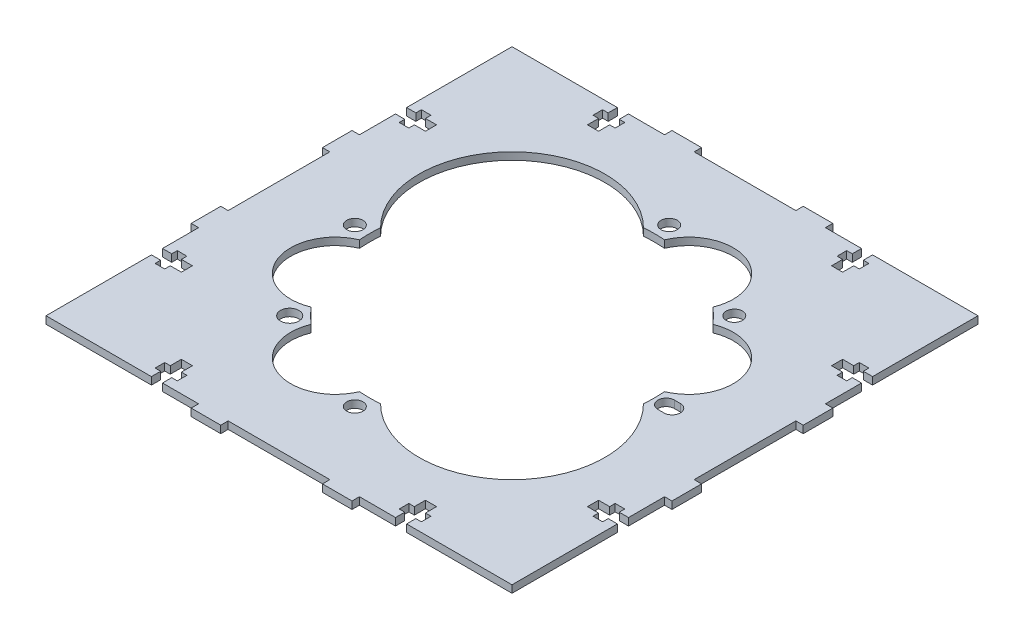
SolidWorks part; units mm, degrees
ref_plane "前视基准面" through (0, 0, 0) normal (0, 0, 1) x (1, 0, 0)
ref_plane "上视基准面" through (0, 0, 0) normal (0, 1, 0) x (1, 0, 0)
ref_plane "右视基准面" through (0, 0, 0) normal (1, 0, 0) x (0, 0, -1)
sketch "草图1" plane through (0, 0, 0) normal (0, 1, 0) x (1, 0, 0)
  line L529 (159.7547, 48.9956) -> (150.0047, 48.9956)
  line L530 (147.0047, 46.4956) -> (145.5047, 46.4956)
  line L531 (150.0047, 46.4956) -> (151.5047, 46.4956)
  line L532 (150.0047, 48.9956) -> (150.0047, 46.4956)
  line L533 (145.5047, 46.4956) -> (145.5047, 43.8956)
  line L534 (145.5047, 43.8956) -> (147.0047, 43.8956)
  line L535 (147.0047, 43.8956) -> (147.0047, 40.8956)
  line L536 (150.0047, 40.8956) -> (147.0047, 40.8956)
  line L537 (150.0047, 43.8956) -> (150.0047, 40.8956)
  line L538 (151.5047, 43.8956) -> (150.0047, 43.8956)
  line L539 (151.5047, 46.4956) -> (151.5047, 43.8956)
  line L540 (147.0047, 46.4956) -> (147.0047, 48.9956)
  line L541 (213.0047, 48.9956) -> (203.2547, 48.9956)
  line L542 (211.5047, 46.4956) -> (211.5047, 43.8956)
  line L543 (216.0047, 46.4956) -> (216.0047, 48.9956)
  line L544 (211.5047, 43.8956) -> (213.0047, 43.8956)
  line L545 (213.0047, 43.8956) -> (213.0047, 40.8956)
  line L546 (213.0047, 40.8956) -> (216.0047, 40.8956)
  line L547 (216.0047, 43.8956) -> (216.0047, 40.8956)
  line L548 (217.5047, 43.8956) -> (216.0047, 43.8956)
  line L549 (217.5047, 46.4956) -> (217.5047, 43.8956)
  line L550 (213.0047, 48.9956) -> (213.0047, 46.4956)
  line L551 (213.0047, 46.4956) -> (211.5047, 46.4956)
  line L552 (216.0047, 46.4956) -> (217.5047, 46.4956)
  line L554 (203.2547, 48.9956) -> (203.2547, 50.9956)
  line L555 (195.2547, 50.9956) -> (195.2547, 48.9956)
  line L556 (195.2547, 48.9956) -> (167.7547, 48.9956)
  line L557 (159.7547, 50.9956) -> (167.7547, 50.9956)
  line L558 (167.7547, 48.9956) -> (167.7547, 50.9956)
  line L559 (159.7547, 50.9956) -> (159.7547, 48.9956)
  line L560 (203.2547, 50.9956) -> (195.2547, 50.9956)
  line L598 (217.0047, 48.9956) -> (216.0047, 48.9956)
  line L602 (244.5047, 7.7456) -> (244.5047, 17.4956)
  line L603 (242.0047, 20.4956) -> (242.0047, 21.9956)
  line L604 (147.0047, 48.9956) -> (138.6047, 48.9956)
  line L605 (242.0047, 17.4956) -> (242.0047, 15.9956)
  line L606 (244.5047, 17.4956) -> (242.0047, 17.4956)
  line L607 (181.5047, -77.0044) -> (181.5047, -65.0044) construction
  line L608 (242.0047, 21.9956) -> (239.4047, 21.9956)
  line L609 (138.6047, 48.9956) -> (133.5047, 48.9956)
  line L613 (217.0047, 48.9956) -> (229.5047, 48.9956)
  line L614 (239.4047, 21.9956) -> (239.4047, 20.4956)
  line L615 (239.4047, 20.4956) -> (236.4047, 20.4956)
  line L616 (236.4047, 17.4956) -> (236.4047, 20.4956)
  line L617 (239.4047, 17.4956) -> (236.4047, 17.4956)
  line L618 (239.4047, 15.9956) -> (239.4047, 17.4956)
  line L619 (242.0047, 15.9956) -> (239.4047, 15.9956)
  line L620 (242.0047, 20.4956) -> (244.5047, 20.4956)
  line L621 (244.5047, -45.5044) -> (244.5047, -35.7544)
  line L622 (242.0047, -44.0044) -> (239.4047, -44.0044)
  line L623 (242.0047, -48.5044) -> (244.5047, -48.5044)
  line L624 (239.4047, -44.0044) -> (239.4047, -45.5044)
  line L625 (239.4047, -45.5044) -> (236.4047, -45.5044)
  line L626 (236.4047, -45.5044) -> (236.4047, -48.5044)
  line L627 (239.4047, -48.5044) -> (236.4047, -48.5044)
  line L628 (239.4047, -50.0044) -> (239.4047, -48.5044)
  line L629 (242.0047, -50.0044) -> (239.4047, -50.0044)
  line L630 (244.5047, -45.5044) -> (242.0047, -45.5044)
  line L631 (242.0047, -45.5044) -> (242.0047, -44.0044)
  line L632 (242.0047, -48.5044) -> (242.0047, -50.0044)
  line L633 (244.5047, -35.7544) -> (246.5047, -35.7544)
  line L634 (246.5047, -27.7544) -> (244.5047, -27.7544)
  line L635 (244.5047, -27.7544) -> (244.5047, -0.2544)
  line L636 (246.5047, 7.7456) -> (246.5047, -0.2544)
  line L637 (244.5047, -0.2544) -> (246.5047, -0.2544)
  line L638 (246.5047, 7.7456) -> (244.5047, 7.7456)
  line L639 (246.5047, -35.7544) -> (246.5047, -27.7544)
  line L640 (244.5047, -49.5044) -> (244.5047, -48.5044)
  line L641 (244.5047, 20.4956) -> (244.5047, 28.8956)
  line L642 (244.5047, 28.8956) -> (244.5047, 33.9956)
  line L643 (244.5047, -49.5044) -> (244.5047, -62.0044)
  line L644 (203.2547, -77.0044) -> (213.0047, -77.0044)
  line L645 (216.0047, -74.5044) -> (217.5047, -74.5044)
  line L646 (213.0047, -74.5044) -> (211.5047, -74.5044)
  line L647 (213.0047, -77.0044) -> (213.0047, -74.5044)
  line L648 (217.5047, -74.5044) -> (217.5047, -71.9044)
  line L649 (217.5047, -71.9044) -> (216.0047, -71.9044)
  line L650 (216.0047, -71.9044) -> (216.0047, -68.9044)
  line L651 (213.0047, -68.9044) -> (216.0047, -68.9044)
  line L652 (213.0047, -71.9044) -> (213.0047, -68.9044)
  line L653 (211.5047, -71.9044) -> (213.0047, -71.9044)
  line L654 (211.5047, -74.5044) -> (211.5047, -71.9044)
  line L655 (216.0047, -74.5044) -> (216.0047, -77.0044)
  line L656 (150.0047, -77.0044) -> (159.7547, -77.0044)
  line L657 (151.5047, -74.5044) -> (151.5047, -71.9044)
  line L658 (147.0047, -74.5044) -> (147.0047, -77.0044)
  line L659 (151.5047, -71.9044) -> (150.0047, -71.9044)
  line L660 (150.0047, -71.9044) -> (150.0047, -68.9044)
  line L661 (150.0047, -68.9044) -> (147.0047, -68.9044)
  line L662 (147.0047, -71.9044) -> (147.0047, -68.9044)
  line L663 (145.5047, -71.9044) -> (147.0047, -71.9044)
  line L664 (145.5047, -74.5044) -> (145.5047, -71.9044)
  line L665 (150.0047, -77.0044) -> (150.0047, -74.5044)
  line L666 (150.0047, -74.5044) -> (151.5047, -74.5044)
  line L667 (147.0047, -74.5044) -> (145.5047, -74.5044)
  line L668 (159.7547, -77.0044) -> (159.7547, -79.0044)
  line L669 (167.7547, -79.0044) -> (167.7547, -77.0044)
  line L670 (167.7547, -77.0044) -> (195.2547, -77.0044)
  line L671 (203.2547, -79.0044) -> (195.2547, -79.0044)
  line L672 (195.2547, -77.0044) -> (195.2547, -79.0044)
  line L673 (203.2547, -79.0044) -> (203.2547, -77.0044)
  line L674 (159.7547, -79.0044) -> (167.7547, -79.0044)
  line L675 (146.0047, -77.0044) -> (147.0047, -77.0044)
  line L676 (216.0047, -77.0044) -> (224.4047, -77.0044)
  line L677 (224.4047, -77.0044) -> (229.5047, -77.0044)
  line L678 (146.0047, -77.0044) -> (133.5047, -77.0044)
  line L679 (118.5047, -35.7544) -> (118.5047, -45.5044)
  line L680 (121.0047, -48.5044) -> (121.0047, -50.0044)
  line L681 (121.0047, -45.5044) -> (121.0047, -44.0044)
  line L682 (118.5047, -45.5044) -> (121.0047, -45.5044)
  line L683 (121.0047, -50.0044) -> (123.6047, -50.0044)
  line L684 (123.6047, -50.0044) -> (123.6047, -48.5044)
  line L685 (123.6047, -48.5044) -> (126.6047, -48.5044)
  line L686 (126.6047, -45.5044) -> (126.6047, -48.5044)
  line L687 (123.6047, -45.5044) -> (126.6047, -45.5044)
  line L688 (123.6047, -44.0044) -> (123.6047, -45.5044)
  line L689 (121.0047, -44.0044) -> (123.6047, -44.0044)
  line L690 (121.0047, -48.5044) -> (118.5047, -48.5044)
  line L691 (118.5047, 17.4956) -> (118.5047, 7.7456)
  line L692 (121.0047, 15.9956) -> (123.6047, 15.9956)
  line L693 (121.0047, 20.4956) -> (118.5047, 20.4956)
  line L694 (123.6047, 15.9956) -> (123.6047, 17.4956)
  line L695 (123.6047, 17.4956) -> (126.6047, 17.4956)
  line L696 (126.6047, 17.4956) -> (126.6047, 20.4956)
  line L697 (123.6047, 20.4956) -> (126.6047, 20.4956)
  line L698 (123.6047, 21.9956) -> (123.6047, 20.4956)
  line L699 (121.0047, 21.9956) -> (123.6047, 21.9956)
  line L700 (118.5047, 17.4956) -> (121.0047, 17.4956)
  line L701 (121.0047, 17.4956) -> (121.0047, 15.9956)
  line L702 (121.0047, 20.4956) -> (121.0047, 21.9956)
  line L703 (118.5047, 7.7456) -> (116.5047, 7.7456)
  line L704 (116.5047, -0.2544) -> (118.5047, -0.2544)
  line L705 (118.5047, -0.2544) -> (118.5047, -27.7544)
  line L706 (116.5047, -35.7544) -> (116.5047, -27.7544)
  line L707 (118.5047, -27.7544) -> (116.5047, -27.7544)
  line L708 (116.5047, -35.7544) -> (118.5047, -35.7544)
  line L709 (116.5047, 7.7456) -> (116.5047, -0.2544)
  line L710 (118.5047, 21.4956) -> (118.5047, 20.4956)
  line L711 (118.5047, -48.5044) -> (118.5047, -56.9044)
  line L712 (118.5047, -56.9044) -> (118.5047, -62.0044)
  line L713 (118.5047, 21.4956) -> (118.5047, 33.9956)
  line L714 (133.5047, 48.9956) -> (118.5047, 48.9956)
  line L715 (118.5047, 48.9956) -> (118.5047, 33.9956)
  line L716 (229.5047, 48.9956) -> (244.5047, 48.9956)
  line L717 (244.5047, 48.9956) -> (244.5047, 33.9956)
  line L718 (244.5047, -62.0044) -> (244.5047, -77.0044)
  line L719 (244.5047, -77.0044) -> (229.5047, -77.0044)
  line L720 (133.5047, -77.0044) -> (118.5047, -77.0044)
  line L721 (118.5047, -77.0044) -> (118.5047, -62.0044)
  line L722 (223.1897, -14.0044) -> (224.8197, -14.0044) construction
  line L725 (223.1897, -11.7902) -> (224.8197, -11.7902)
  line L726 (223.1897, -16.2186) -> (224.8197, -16.2186)
  circle A5 centre (181.5047, -56.5044) radius 2.2
  circle A6 centre (151.4527, -44.0564) radius 2.2 construction
  circle A7 centre (139.0047, -14.0044) radius 2.2
  circle A11 centre (224.0047, -14.0044) radius 2.2 construction
  circle A15 centre (211.5568, 16.0476) radius 2.2
  circle A18 centre (181.5047, 28.4982) radius 2.2
  circle A40 centre (151.4527, -44.0564) radius 5 construction
  arc A41 (156.3736, -43.1708) -> (152.3384, -39.1355) centre (181.5047, -14.0044) cw
  arc A42 (143.1106, -16.8578) -> (143.1106, -11.151) centre (181.5047, -14.0044) cw
  circle A46 centre (181.5047, -14.0044) radius 38.5 construction
  arc A47 (178.6514, 24.3897) -> (184.3581, 24.3897) centre (181.5047, -14.0044) cw
  arc A49 (206.6358, 15.162) -> (210.6711, 11.1267) centre (181.5047, -14.0044) cw
  arc A50 (223.1897, -11.7902) -> (223.1897, -16.2186) centre (223.1897, -14.0044) ccw
  arc A51 (224.8197, -16.2186) -> (224.8197, -11.7902) centre (224.8197, -14.0044) ccw
  arc A52 (219.8989, -11.151) -> (219.8989, -16.8578) centre (181.5047, -14.0044) cw
  arc A53 (152.3384, -39.1355) -> (143.1106, -16.8578) centre (147.7245, -27.9966) cw
  arc A54 (184.3581, -52.3985) -> (178.6514, -52.3985) centre (181.5047, -14.0044) cw
  arc A55 (152.3384, 11.1267) -> (156.3736, 15.162) centre (181.5047, -14.0044) cw [skipped]
  arc A56 (210.6711, -39.1355) -> (206.6358, -43.1708) centre (181.5047, -14.0044) cw [skipped]
  arc A57 (178.6514, -52.3985) -> (156.3736, -43.1708) centre (167.5125, -47.7846) cw
  arc A58 (210.6711, 11.1267) -> (219.8989, -11.151) centre (215.285, -0.0122) cw
  arc A59 (184.3581, 24.3897) -> (206.6358, 15.162) centre (195.497, 19.7759) cw
  arc A60 (219.8989, -16.8578) -> (184.3581, -52.3985) centre (202.1285, -34.6281) cw
  arc A61 (143.1106, -11.151) -> (178.6514, 24.3897) centre (160.881, 6.6193) cw
  circle A62 centre (151.4527, -44.0564) radius 2.5
  point P0 (181.5047, -14.0044)
  point P21 (235.9047, -47.5044)
  point P46 (235.9047, 18.4956)
  point P73 (148.0047, -68.4044)
  point P97 (215.0047, 40.3956)
  point P129 (149.0047, 40.3956)
  point P130 (214.0047, -68.4044)
  point P148 (127.1047, 19.4956)
  point P169 (127.1047, -46.5044)
  point P192 (224.0047, -14.0044)
  dimension "D2" = 1.63
  dimension "D1" = 8
  dimension "D3" = 4
extrude "凸台-拉伸1" add sketch "草图1" along normal blind 2
sketch "草图8" plane through (0, 0, -48.9956) normal (0, 0, -1) x (-1, 0, 0)
  line L0 (-213.0047, 0) -> (-216.0047, 2)
  circle A0 centre (-214.5047, 1) radius 1.5
sketch "草图9" plane through (244.5047, 0, 0) normal (1, 0, 0) x (0, 0, -1)
  line L0 (20.4956, 1) -> (17.4956, 1) construction
  line L1 (20.4956, 2) -> (20.4956, 0) construction
  line L2 (17.4956, 2) -> (17.4956, 0) construction
  circle A0 centre (18.9956, 1) radius 1.5
